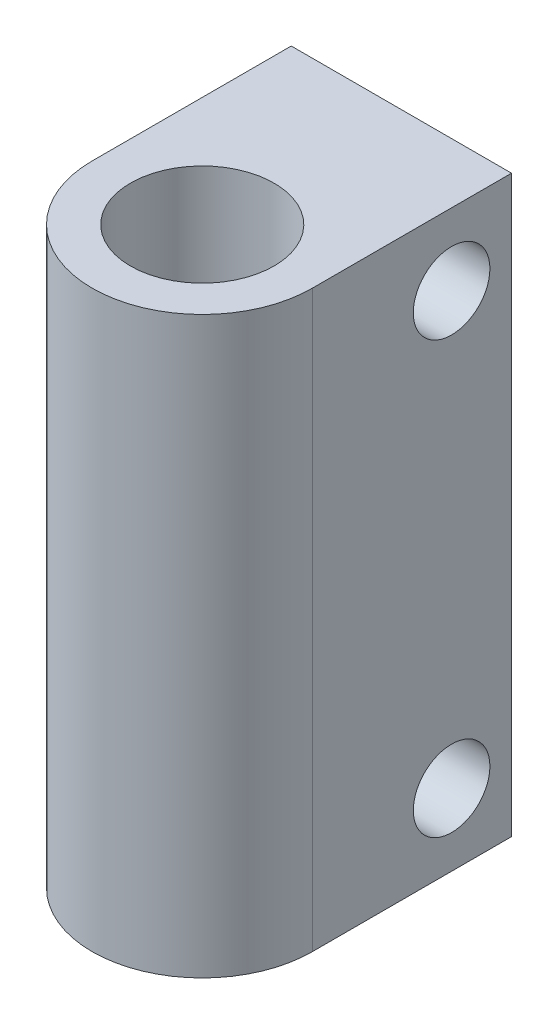
SolidWorks part; units mm, degrees
ref_plane "Front Plane" through (0, 0, 0) normal (0, 0, 1) x (1, 0, 0)
ref_plane "Top Plane" through (0, 0, 0) normal (0, 1, 0) x (1, 0, 0)
ref_plane "Right Plane" through (0, 0, 0) normal (1, 0, 0) x (0, 0, -1)
sketch "Sketch1" plane through (0, 0, 0) normal (0, 1, 0) x (1, 0, 0)
  line L0 (-11.5, 0) -> (-11.5, 20.7934)
  line L1 (11.5, 0) -> (11.5, 20.7934)
  line L2 (11.5, 20.7934) -> (-11.5, 20.7934)
  circle A0 centre (0, 0) radius 7.5
  arc A1 (-11.5, 0) -> (11.5, 0) centre (0, 0) ccw
  dimension "D1" = 15
  dimension "D2" = 4
extrude "Boss-Extrude1" add sketch "Sketch1" along normal blind 60
sketch "Sketch2" plane through (11.5, 0, 0) normal (1, 0, 0) x (0, 0, -1)
  line L0 (14.5373, 60) -> (14.5373, 0) construction
  line L1 (0, 60) -> (20.7934, 60) construction
  line L2 (0, 0) -> (20.7934, 0) construction
  circle A0 centre (14.5373, 52.5) radius 4
  circle A1 centre (14.5373, 7.5) radius 4
  point P10 (14.5373, 30)
  dimension "D1" = 8
  dimension "D2" = 8
  dimension "D3" = 45
  dimension "D4" = 22.5
extrude "Cut-Extrude1" cut sketch "Sketch2" against normal blind 50
